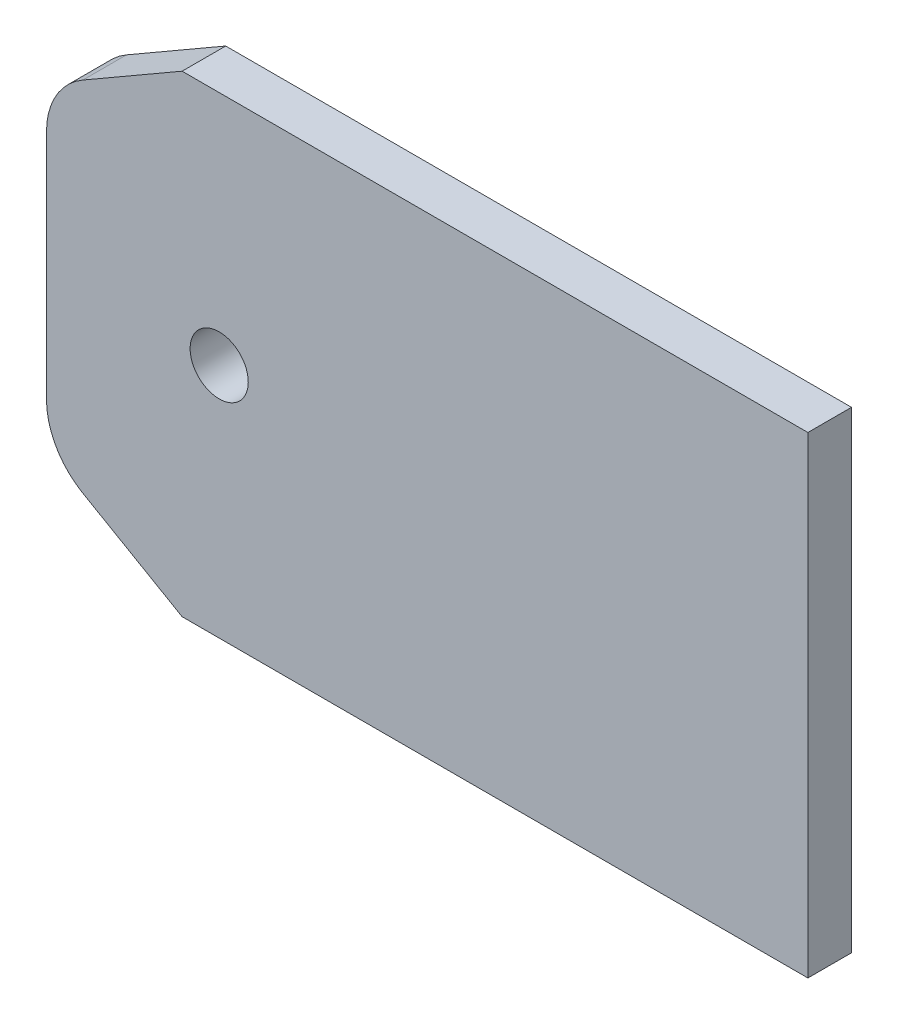
SolidWorks part; units mm, degrees
ref_plane "Front Plane" through (0, 0, 0) normal (0, 0, 1) x (1, 0, 0)
ref_plane "Top Plane" through (0, 0, 0) normal (0, 1, 0) x (1, 0, 0)
ref_plane "Right Plane" through (0, 0, 0) normal (1, 0, 0) x (0, 0, -1)
sketch "Sketch1" plane through (0, 0, 0) normal (0, 0, 1) x (1, 0, 0)
  line L0 (-37.7876, 307.9326) -> (-123.8876, 307.9326)
  line L1 (-142.5453, 259.4776) -> (-142.5453, 291.3876)
  line L7 (-37.7876, 242.9326) -> (-123.8876, 242.9326)
  line L8 (-123.8876, 242.9326) -> (-137.5451, 250.8172)
  line L10 (-123.8876, 307.9326) -> (-137.5451, 300.048)
  line L13 (-37.7876, 242.9326) -> (-37.7876, 307.9326)
  arc A0 (-137.5451, 300.048) -> (-142.5453, 291.3876) centre (-132.5453, 291.3876) ccw
  circle A2 centre (-118.7853, 275.4326) radius 4
  arc A3 (-137.5451, 250.8172) -> (-142.5453, 259.4776) centre (-132.5453, 259.4776) cw
  point P6 (-120.8997, 283.7282)
  point P7 (-115.0593, 246.3198)
  point P12 (0, 0)
  point P14 (0, 0)
  point P16 (0, 0)
  point P18 (15.2756, 0.8198)
  dimension "D7" = 15.77
  dimension "D9" = 10
  dimension "D10" = 10
  dimension "D15" = 8
  dimension "D1" = 15.77
  dimension "D2" = 65
  dimension "D3" = 86.1
  dimension "D4" = 86.1
  dimension "D5" = 90
  dimension "D6" = 90
  dimension "D8" = 31.91
  dimension "D11" = 242.9326
  dimension "D12" = 37.7876
  dimension "D13" = 23.76
  dimension "D14" = 32.5
  dimension "D16" = 242.9326
extrude "Boss-Extrude1" add sketch "Sketch1" along normal blind 6 separate body
